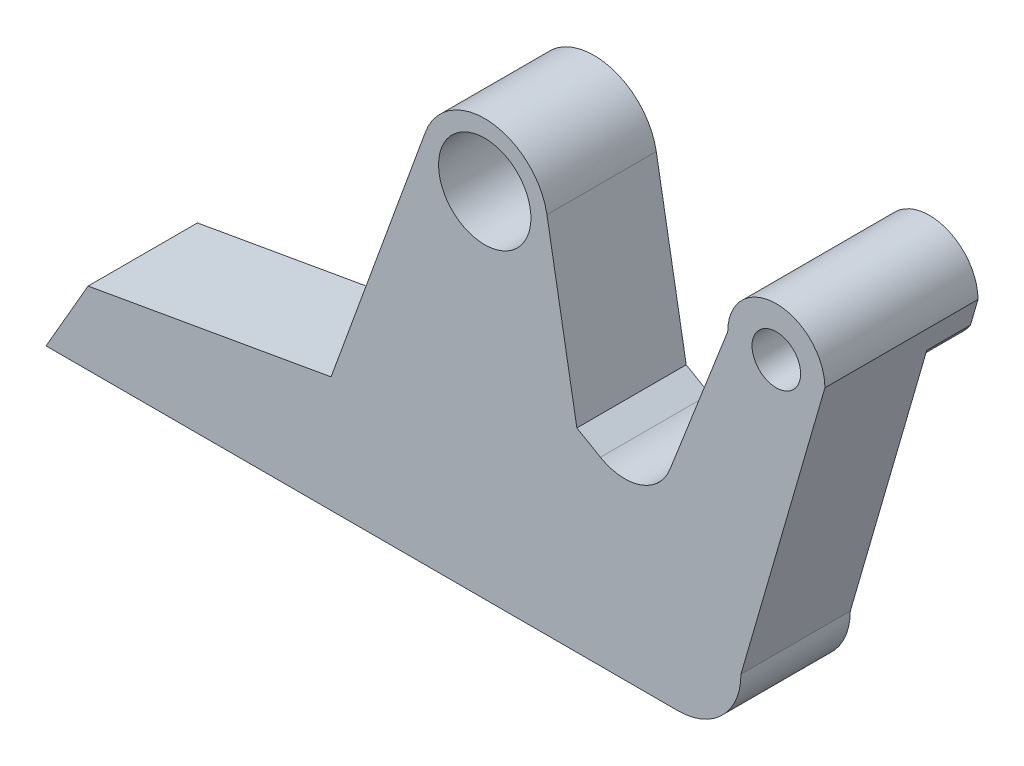
SolidWorks part; units mm, degrees
ref_plane "Front Plane" through (0, 0, 0) normal (0, 0, 1) x (1, 0, 0)
ref_plane "Top Plane" through (0, 0, 0) normal (0, 1, 0) x (1, 0, 0)
ref_plane "Right Plane" through (0, 0, 0) normal (1, 0, 0) x (0, 0, -1)
sketch "Sketch1" plane through (0, 0, 0) normal (0, 0, 1) x (1, 0, 0)
  line L0 (78.0582, 77.1119) -> (58.6603, 23.8163)
  line L5 (103.0768, 74.9231) -> (109.2346, 40)
  line L6 (58.6603, 23.8163) -> (8.6603, 15)
  line L7 (8.6603, 15) -> (0, 0)
  line L8 (0, 0) -> (130, 0)
  line L9 (109.2346, 40) -> (136.5, 24.2583)
  line L10 (140.2742, 72.6656) -> (117, 13)
  line L12 (160.2742, 72.6656) -> (143, 13)
  line L14 (90.2742, 72.6656) -> (219.4605, 72.6656) construction
  circle A0 centre (90.2742, 72.6656) radius 13
  circle A1 centre (130, 13) radius 13
  circle A2 centre (90.2742, 72.6656) radius 9.5
  circle A3 centre (130, 13) radius 3.5 construction
  circle A4 centre (150.2742, 72.6656) radius 10
  circle A5 centre (150.2742, 72.6656) radius 5
  dimension "D3" = 26
  dimension "D4" = 26
  dimension "D5" = 19
  dimension "D6" = 7
  dimension "D14" = 20
  dimension "D15" = 10
  dimension "D1" = 60
  dimension "D2" = 10
  dimension "D7" = 50
  dimension "D8" = 15
  dimension "D9" = 130
  dimension "D10" = 30
  dimension "D11" = 40
  dimension "D12" = 70
  dimension "D13" = 80
  dimension "D16" = 60
extrude "Boss-Extrude1" add sketch "Sketch1" along normal blind 22.5 contours A1 L10 L9 L5 A0 L0 L6 L7 L8 | A0 A2 | A1 L9 L10 | A1 L10 | A4 L10 L9 A1 L12 | L12 A4 A5
ref_plane "Plane1" through (0, 0, 0) normal (-1, 0, 0) x (0, 0, -1)
sketch "Sketch6" plane through (0, 0, 0) normal (-1, 0, 0) x (0, 0, -1)
  line L0 (-22.5, 0) -> (0, 0) construction
  line L1 (-14.25, 0) -> (-8.25, 0)
  line L2 (-14.25, 0) -> (-14.25, -3)
  line L3 (-14.25, -3) -> (-8.25, -3)
  line L4 (-8.25, 0) -> (-8.25, -3)
  line L5 (-11.25, 0) -> (-11.25, -8.4365) construction
  line L6 (-17.25, -3) -> (-5.25, -3)
  line L7 (-17.25, -3) -> (-17.25, -6)
  line L8 (-17.25, -6) -> (-5.25, -6)
  line L9 (-5.25, -3) -> (-5.25, -6)
  point P6 (-11.25, 0)
  point P8 (-11.25, 0)
  point P14 (-11.25, -6)
  dimension "D1" = 3
  dimension "D2" = 6
  dimension "D3" = 12
  dimension "D4" = 3
extrude "Cut-Extrude2" cut sketch "Sketch6" against normal up to vertex (130 mm away) contours L1 L5 L6 L4 | L6 L5 L8 L9 | L5 L1 L2 L3 | L5 L3 L6 L7 L8
fillet "Fillet1" radius 10 1 edges at (124.1688, 31.3778, 11.25)
sketch "Sketch7" plane through (0, 0, 22.5) normal (0, 0, 1) x (1, 0, 0)
  circle A0 centre (150.2742, 72.6656) radius 5
  circle A1 centre (150.2742, 72.6656) radius 10
  circle A2 centre (150.2742, 72.6656) radius 5 construction
  arc A3 (160.2742, 72.6656) -> (140.2742, 72.6656) centre (150.2742, 72.6656) ccw construction
  line M4 (143, 13) -> (160.2742, 72.6656)
  arc M5 (160.2742, 72.6656) -> (140.2742, 72.6656) centre (150.2742, 72.6656) ccw
  circle M16 centre (150.2742, 72.6656) radius 5
extrude "Boss-Extrude2" add sketch "Sketch7" along normal blind 9 contours A1 M5 M4 M16
mirror "Mirror1" about plane through (0, 0, 0) normal (0, 0, 1) of bodies 104
delete or keep bodies "Body-Delete/Keep 1" type delete bodies bodies 104
